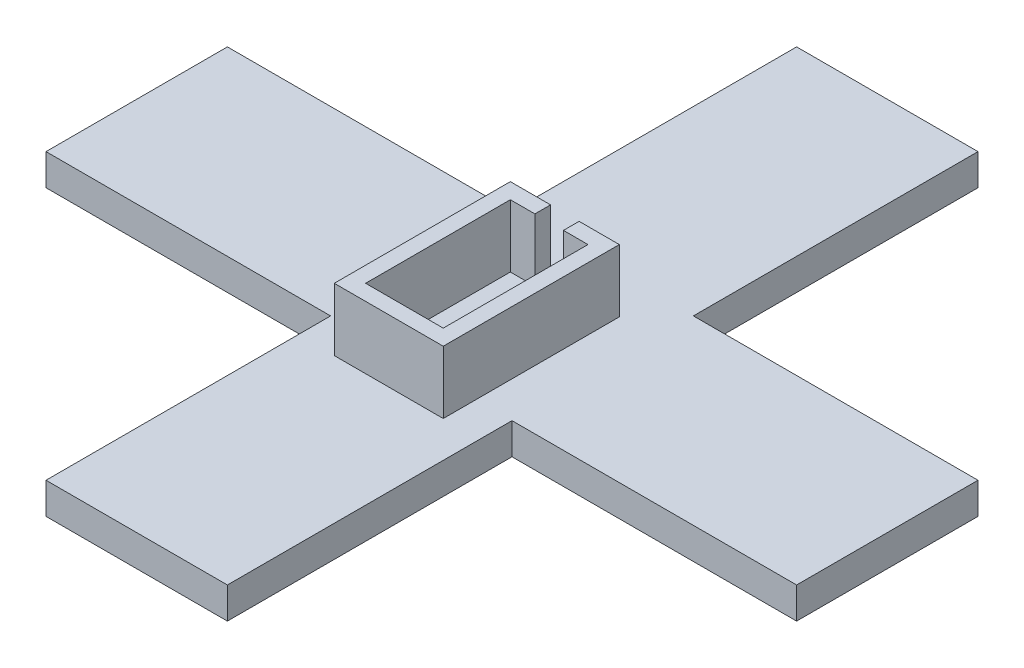
SolidWorks part; units mm, degrees
ref_plane "Front Plane" through (0, 0, 0) normal (0, 0, 1) x (1, 0, 0)
ref_plane "Top Plane" through (0, 0, 0) normal (0, 1, 0) x (1, 0, 0)
ref_plane "Right Plane" through (0, 0, 0) normal (1, 0, 0) x (0, 0, -1)
sketch "Sketch21" plane through (0, 0, 0) normal (0, 1, 0) x (1, 0, 0)
  line L22 (0, 59.92) -> (-14.48, 59.92)
  line L23 (-14.48, 59.92) -> (-14.48, 14.48)
  line L24 (-14.48, 14.48) -> (-59.92, 14.48)
  line L25 (-59.92, -14.48) -> (-14.48, -14.48)
  line L26 (-14.48, -14.48) -> (-14.48, -59.92)
  line L27 (-14.48, -59.92) -> (0, -59.92)
  line L28 (0, -59.92) -> (14.48, -59.92)
  line L29 (14.48, -59.92) -> (14.48, -14.48)
  line L30 (14.48, -14.48) -> (59.92, -14.48)
  line L31 (59.92, 14.48) -> (14.48, 14.48)
  line L32 (14.48, 14.48) -> (14.48, 59.92)
  line L33 (14.48, 59.92) -> (0, 59.92)
  line L34 (-59.92, 0) -> (-59.92, 14.48)
  line L35 (-59.92, -14.48) -> (-59.92, 0)
  line L36 (59.92, 0) -> (59.92, 14.48)
  line L37 (59.92, 0) -> (59.92, -14.48)
  dimension "D1" = 45.44
  dimension "D2" = 14.48
  dimension "D3" = 14.48
  dimension "D4" = 119.84
  dimension "D5" = 119.84
  dimension "D13" = 14.48
extrude "Boss-Extrude18" add sketch "Sketch21" along normal blind 5
sketch "Sketch23" plane through (0, 5, 0) normal (0, 1, 0) x (1, 0, 0)
  line L0 (-8.7, 8.435) -> (-2.28, 8.435)
  line L2 (-8.7, 8.435) -> (-8.7, -19.675)
  line L3 (-8.7, -19.675) -> (8.7, -19.675)
  line L4 (8.7, 8.435) -> (8.7, -19.675)
  line L5 (-2.28, 8.435) -> (-2.28, 5.935)
  line L6 (-2.28, 5.935) -> (-6.2, 5.935)
  line L7 (-6.2, 5.935) -> (-6.2, -17.175)
  line L8 (-6.2, -17.175) -> (6.2, -17.175)
  line L9 (6.2, -17.175) -> (6.2, 5.935)
  line L10 (6.2, 5.935) -> (2.28, 5.935)
  line L11 (2.28, 5.935) -> (2.28, 8.435)
  line L12 (2.28, 8.435) -> (8.7, 8.435)
  line L16 (14.48, 59.92) -> (-14.48, 59.92) construction
  point P0 (0, 0)
  dimension "D1" = 6.2
  dimension "D2" = 12.4
  dimension "D3" = 51.485
  dimension "D4" = 23.11
  dimension "D5" = 2.5
  dimension "D6" = 2.5
  dimension "D7" = 2.5
  dimension "D8" = 2.5
  dimension "D9" = 3.92
  dimension "D10" = 3.92
extrude "Boss-Extrude19" add sketch "Sketch23" along normal blind 10
